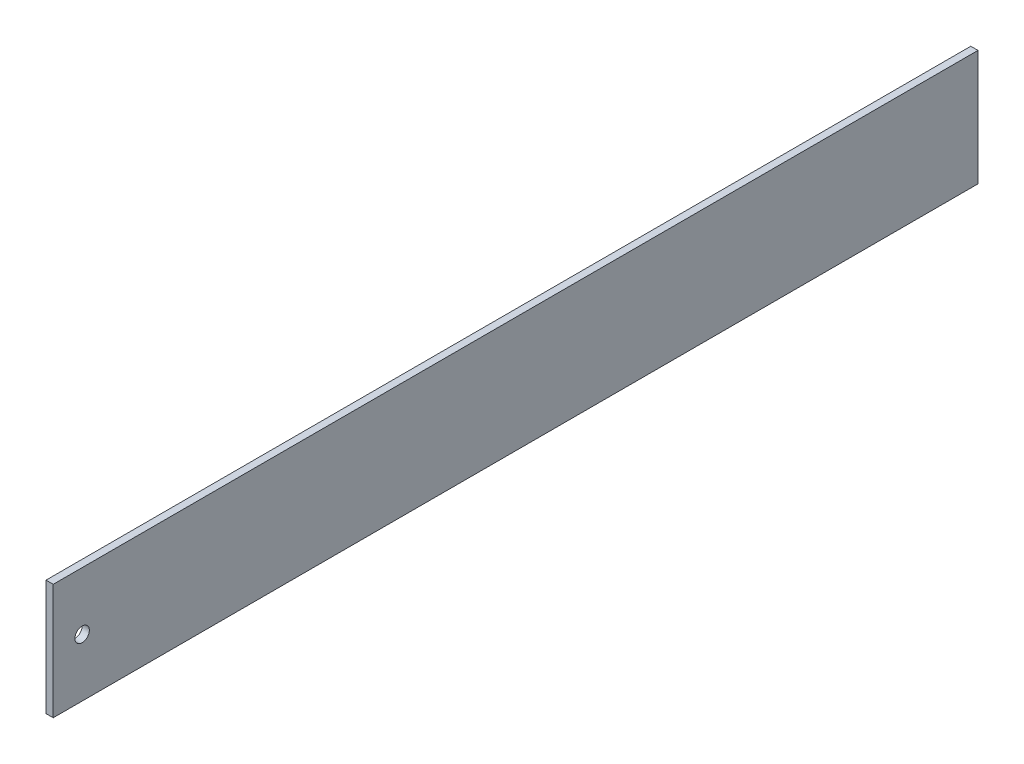
SolidWorks part; units mm, degrees
ref_plane "Front Plane" through (0, 0, 0) normal (0, 0, 1) x (1, 0, 0)
ref_plane "Top Plane" through (0, 0, 0) normal (0, 1, 0) x (1, 0, 0)
ref_plane "Right Plane" through (0, 0, 0) normal (1, 0, 0) x (0, 0, -1)
sketch "Sketch1" plane through (0, 0, 0) normal (1, 0, 0) x (0, 0, -1)
  line L1 (-203.2, 25.4) -> (203.2, 25.4)
  line L2 (-203.2, 25.4) -> (-203.2, -25.4)
  line L3 (-203.2, -25.4) -> (203.2, -25.4)
  line L4 (203.2, 25.4) -> (203.2, -25.4)
  line L5 (-203.2, 25.4) -> (203.2, -25.4) construction
  line L6 (-203.2, -25.4) -> (203.2, 25.4) construction
  point P0 (0, 0)
  dimension "D1" = 50.8
  dimension "D2" = 406.4
extrude "Boss-Extrude1" add sketch "Sketch1" along normal blind 3.175
sketch "Sketch2" plane through (3.175, 0, 0) normal (1, 0, 0) x (0, 0, -1)
  line L0 (-203.2, 25.4) -> (-203.2, -25.4) construction
  circle A0 centre (-190.5, 0) radius 3.175
  dimension "D1" = 12.7
extrude "Cut-Extrude1" cut sketch "Sketch2" against normal up to next
